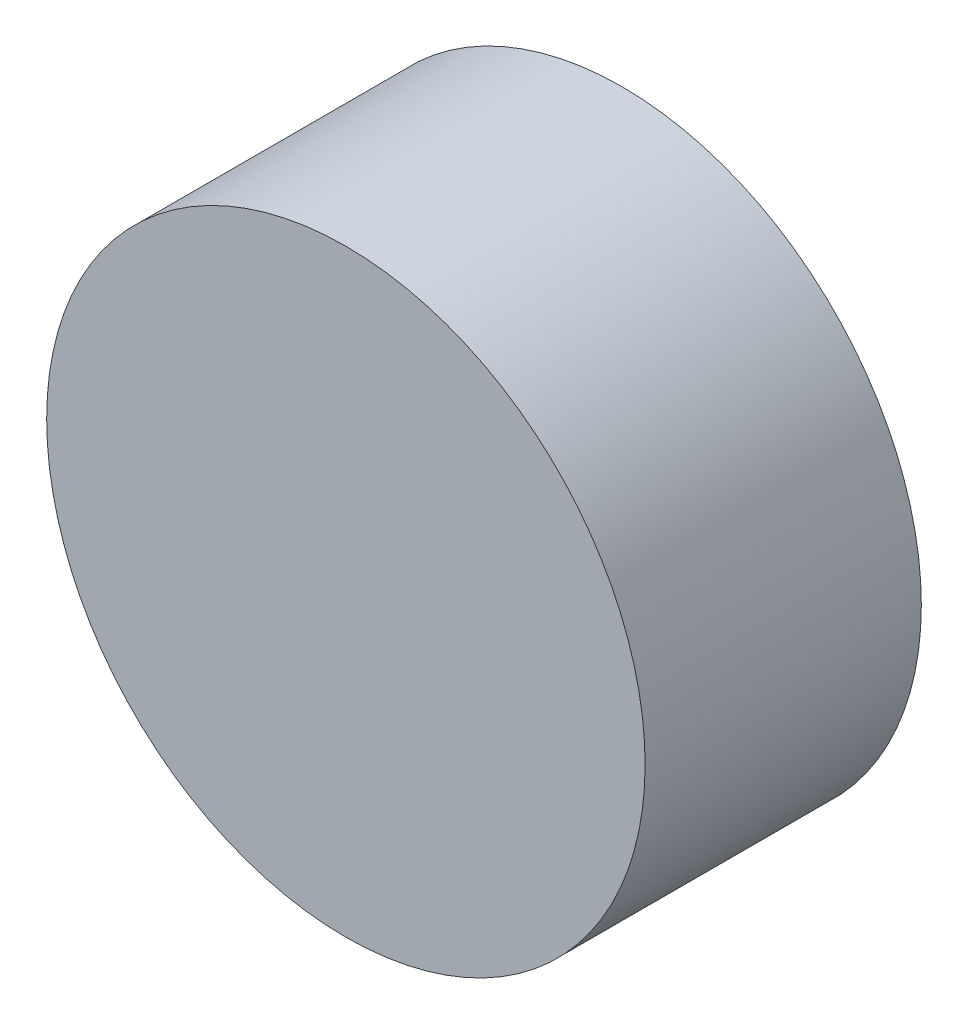
SolidWorks part; units mm, degrees
ref_plane "前基準面" through (0, 0, 0) normal (0, 0, 1) x (1, 0, 0)
ref_plane "上基準面" through (0, 0, 0) normal (0, 1, 0) x (1, 0, 0)
ref_plane "右基準面" through (0, 0, 0) normal (1, 0, 0) x (0, 0, -1)
sketch "草圖1" plane through (0, 0, 0) normal (0, 0, 1) x (1, 0, 0)
  circle A0 centre (0, 0) radius 65
  dimension "D1" = 130
extrude "伸長1" add sketch "草圖1" along normal blind 60
